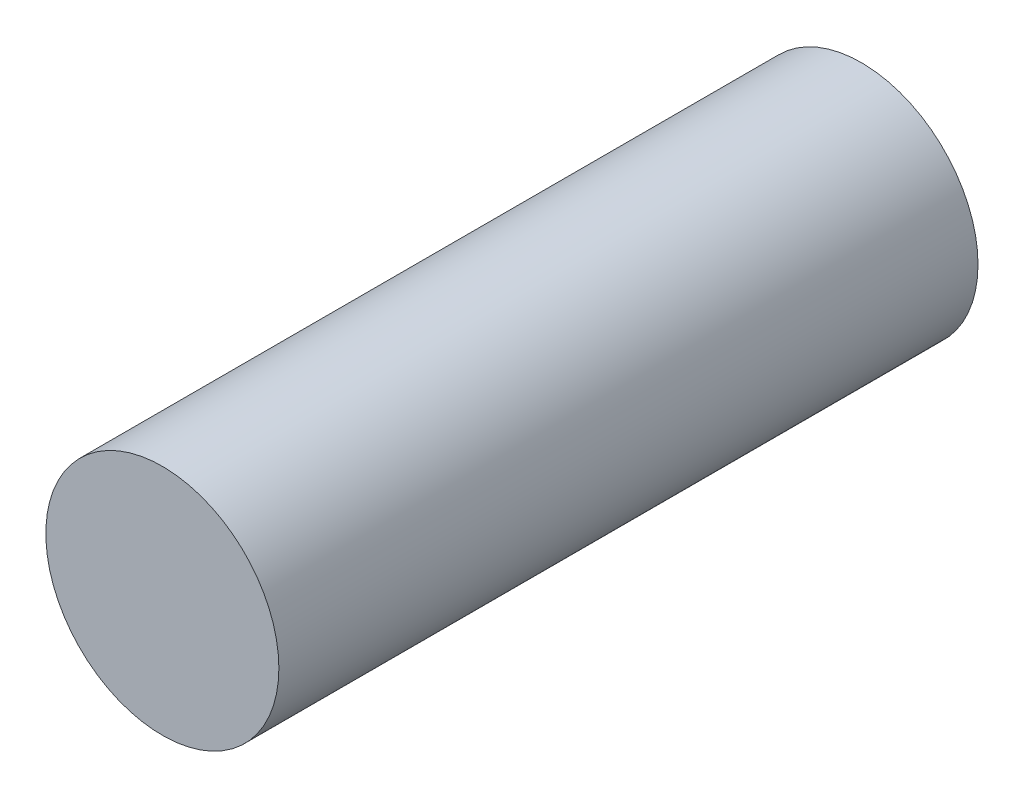
SolidWorks part; units mm, degrees
ref_plane "Ebene vorne" through (0, 0, 0) normal (0, 0, 1) x (1, 0, 0)
ref_plane "Ebene oben" through (0, 0, 0) normal (0, 1, 0) x (1, 0, 0)
ref_plane "Ebene rechts" through (0, 0, 0) normal (1, 0, 0) x (0, 0, -1)
sketch "Skizze1" plane through (0, 0, 0) normal (0, 0, 1) x (1, 0, 0)
  circle A0 centre (0, 0) radius 4
  dimension "D1" = 8
extrude "Aufsatz-Linear austragen1" add sketch "Skizze1" along normal blind 24
